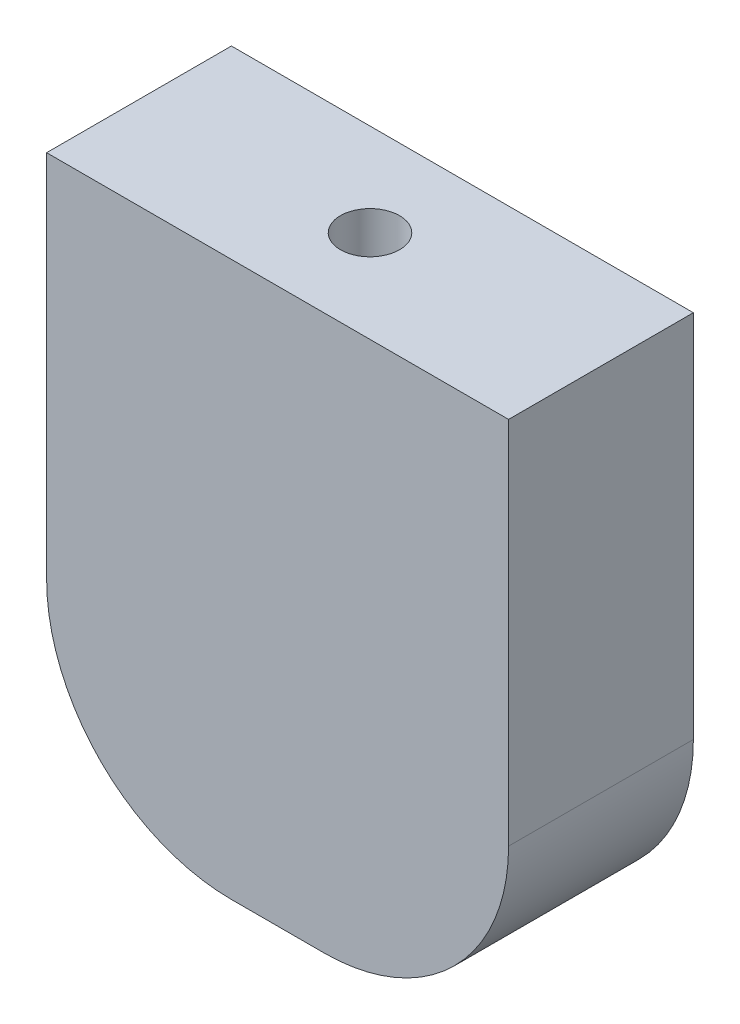
SolidWorks part; units mm, degrees
material "Acrylic (Medium-high impact)"
ref_plane "Front Plane" through (0, 0, 0) normal (0, 0, 1) x (1, 0, 0)
ref_plane "Top Plane" through (0, 0, 0) normal (0, 1, 0) x (1, 0, 0)
ref_plane "Right Plane" through (0, 0, 0) normal (1, 0, 0) x (0, 0, -1)
sketch "Sketch1" plane through (0, 0, 0) normal (0, 0, 1) x (1, 0, 0)
  line L0 (-34.925, 73.66) -> (34.925, 73.66) construction
  line L1 (6.35, 73.66) -> (38.1, 73.66)
  line L2 (6.35, 73.66) -> (6.35, 35.56)
  line L3 (6.35, 35.56) -> (38.1, 35.56)
  line L4 (38.1, 73.66) -> (38.1, 35.56)
  line L5 (53.975, 73.66) -> (34.925, 73.66) construction
  dimension "D1" = 38.1
  dimension "D2" = 31.75
  dimension "D3" = 6.35
extrude "Extrude1" add sketch "Sketch1" along normal mid plane 12.7
fillet "Fillet1" radius 12.7 2 edges at (38.1, 35.56, 0) (6.35, 35.56, 0)
sketch "Sketch2" plane through (0, 73.66, 0) normal (0, 1, 0) x (-1, 0, 0)
  line L0 (-38.1, -6.35) -> (-6.35, -6.35) construction
  circle A0 centre (-22.225, 0) radius 2.032
  point P4 (-22.225, -6.35)
  dimension "D1" = 4.064
extrude "Cut-Extrude1" cut sketch "Sketch2" against normal blind 12.7
